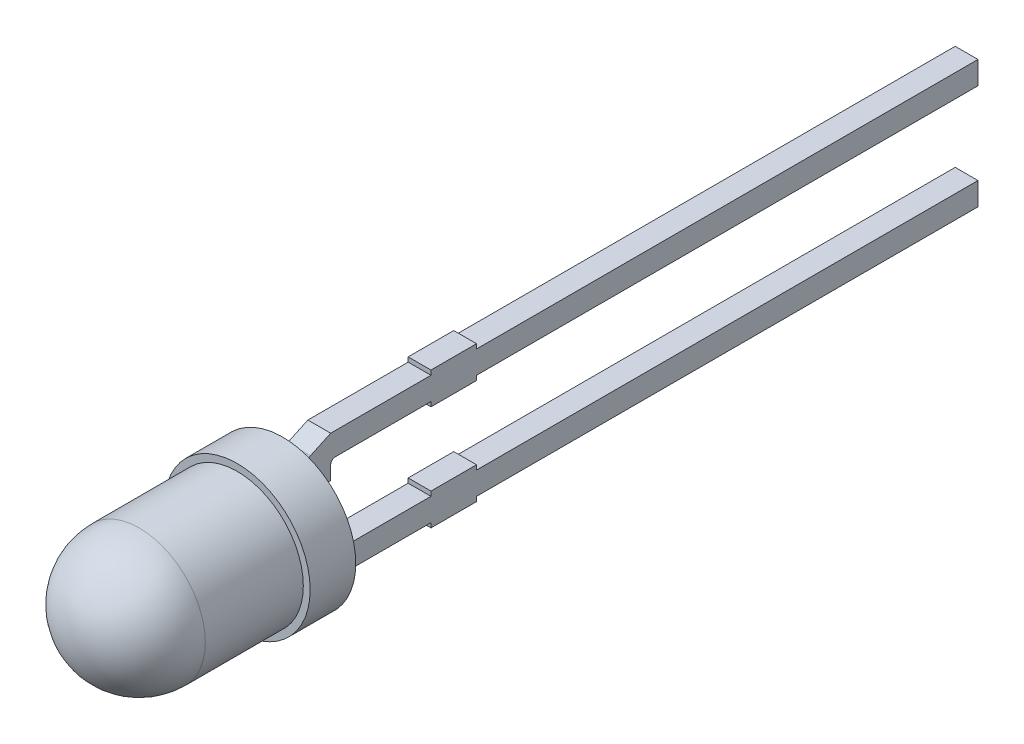
SolidWorks part; units mm, degrees
ref_plane "Front" through (0, 0, 0) normal (0, 0, 1) x (1, 0, 0)
ref_plane "Top" through (0, 0, 0) normal (0, 1, 0) x (1, 0, 0)
ref_plane "Right" through (0, 0, 0) normal (1, 0, 0) x (0, 0, -1)
sketch "Sketch1" plane through (0, 0, 0) normal (1, 0, 0) x (0, 0, -1)
  line L0 (0, 0) -> (76.2974, 0) construction
  line L1 (0, 1.45) -> (2.15, 1.45)
  line L2 (2.15, 1.45) -> (2.15, 1.6)
  line L3 (2.15, 1.6) -> (3.15, 1.6)
  line L4 (3.15, 1.6) -> (3.15, 0)
  line L5 (3.15, 0) -> (-1.45, 0)
  arc A0 (0, 1.45) -> (-1.45, 0) centre (0, 0) ccw
  dimension "D1" = 1.45
  dimension "D2" = 4.6
  dimension "D3" = 1
  dimension "D4" = 1.6
revolve "Revolve1" add sketch "Sketch1" angle 360 about L0
sketch "Sketch2" plane through (0, 0, 0) normal (1, 0, 0) x (0, 0, -1)
  line L0 (3.15, -1.6) -> (3.15, 1.6) construction
  line L1 (3.15, -1.6) -> (3.15, 1.6) construction
  line L2 (3.15, 1.027) -> (3.95, 1.4)
  line L3 (3.95, 1.4) -> (6.15, 1.4)
  line L4 (6.15, 1.4) -> (6.15, 1.5)
  line L5 (6.15, 1.5) -> (7.15, 1.5)
  line L6 (7.15, 1.5) -> (7.15, 1.4)
  line L7 (7.15, 1.4) -> (30.15, 1.4)
  line L8 (30.15, 1.4) -> (30.15, 0.9)
  line L9 (30.15, 0.9) -> (7.15, 0.9)
  line L10 (7.15, 0.9) -> (7.15, 0.8)
  line L11 (7.15, 0.8) -> (6.15, 0.8)
  line L12 (6.15, 0.8) -> (6.15, 0.9)
  line L13 (6.15, 0.9) -> (4.05, 0.9)
  line L14 (3.95, 0.8) -> (3.95, 0.5)
  line L15 (3.95, 0.5) -> (3.15, 0.5)
  line L16 (3.15, 0) -> (7.9733, 0) construction
  line L17 (3.15, 1.027) -> (3.15, 0.5)
  line L18 (3.95, -0.8) -> (3.95, -0.5)
  line L19 (6.15, -0.9) -> (4.05, -0.9)
  line L20 (6.15, -0.8) -> (6.15, -0.9)
  line L21 (7.15, -0.8) -> (6.15, -0.8)
  line L22 (7.15, -0.9) -> (7.15, -0.8)
  line L23 (30.15, -0.9) -> (7.15, -0.9)
  line L24 (30.15, -1.4) -> (30.15, -0.9)
  line L25 (7.15, -1.4) -> (30.15, -1.4)
  line L26 (7.15, -1.5) -> (7.15, -1.4)
  line L27 (6.15, -1.5) -> (7.15, -1.5)
  line L28 (6.15, -1.4) -> (6.15, -1.5)
  line L29 (3.95, -1.4) -> (6.15, -1.4)
  line L30 (3.15, -1.027) -> (3.95, -1.4)
  line L31 (3.15, -1.027) -> (3.15, -0.5)
  line L32 (3.95, -0.5) -> (3.15, -0.5)
  arc A0 (4.05, 0.9) -> (3.95, 0.8) centre (4.05, 0.8) ccw
  arc A1 (4.05, -0.9) -> (3.95, -0.8) centre (4.05, -0.8) cw
  point P19 (3.15, 0)
  dimension "D1" = 0.5
  dimension "D2" = 0.7
  dimension "D3" = 1.4
  dimension "D4" = 0.8
  dimension "D5" = 27
  dimension "D6" = 115
  dimension "D7" = 4
  dimension "D8" = 1
  dimension "D9" = 0.5
  dimension "D10" = 0.1
extrude "Extrude1" add sketch "Sketch2" along normal mid plane 0.5
fillet "Fillet1" radius 0.25 8 edges at (0, -0.5, -3.15) (0, -1.027, -3.15) (-0.25, -0.7635, -3.15) (0, 0.5, -3.15) (-0.25, 0.7635, -3.15) (0, 1.027, -3.15) (0.25, 0.7635, -3.15) (0.25, -0.7635, -3.15)
sketch "Sketch3" plane through (0, 0, 0) normal (1, 0, 0) x (0, 0, -1)
  line L0 (7.15, -1.4) -> (30.15, -1.4) construction
  line L1 (30.15, 1.4) -> (18.15, 1.4)
  line L2 (30.15, 1.4) -> (30.15, -1.4)
  line L3 (30.15, -1.4) -> (18.15, -1.4)
  line L4 (18.15, 1.4) -> (18.15, -1.4)
  line L5 (3.15, -1.6) -> (3.15, 1.6) construction
  dimension "D1" = 15
extrude "Cut-Extrude1" cut sketch "Sketch3" against normal through all both and the other way through all
